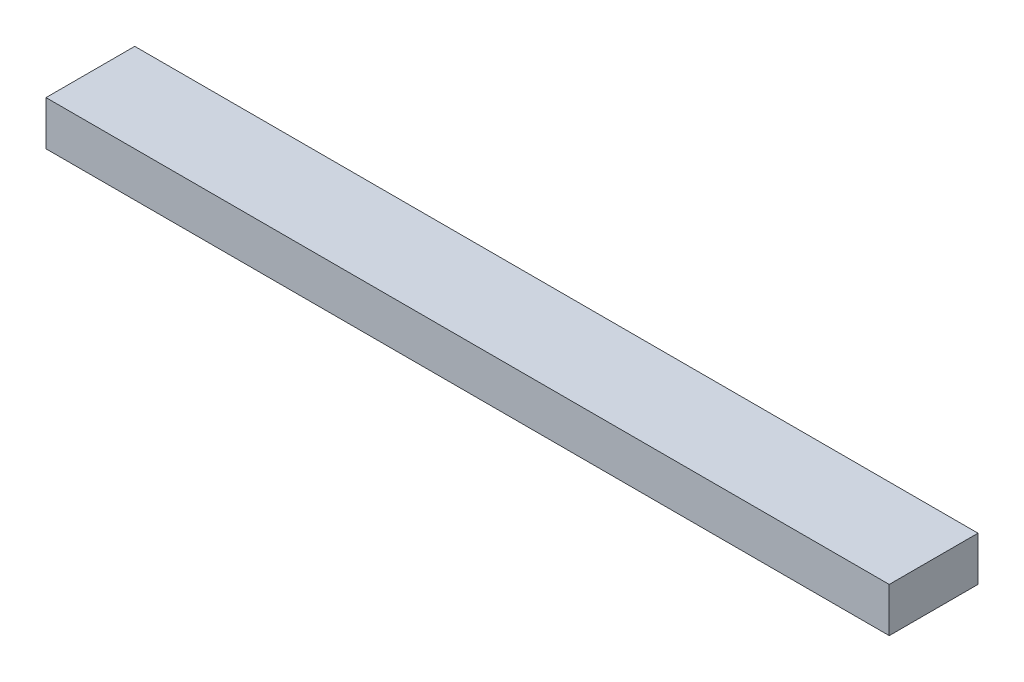
SolidWorks part; units mm, degrees
material "1023 Carbon Steel Sheet (SS)"
ref_plane "Front Plane" through (0, 0, 0) normal (0, 0, 1) x (1, 0, 0)
ref_plane "Top Plane" through (0, 0, 0) normal (0, 1, 0) x (1, 0, 0)
ref_plane "Right Plane" through (0, 0, 0) normal (1, 0, 0) x (0, 0, -1)
sketch "Sketch1" plane through (0, 0, 0) normal (0, 1, 0) x (1, 0, 0)
  line L1 (-53.9406, 28.944) -> (187.3594, 28.944)
  line L2 (-53.9406, 28.944) -> (-53.9406, 3.544)
  line L3 (-53.9406, 3.544) -> (187.3594, 3.544)
  line L4 (187.3594, 28.944) -> (187.3594, 3.544)
  dimension "D1" = 241.3
  dimension "D2" = 25.4
extrude "Boss-Extrude1" add sketch "Sketch1" along normal blind 12.7
